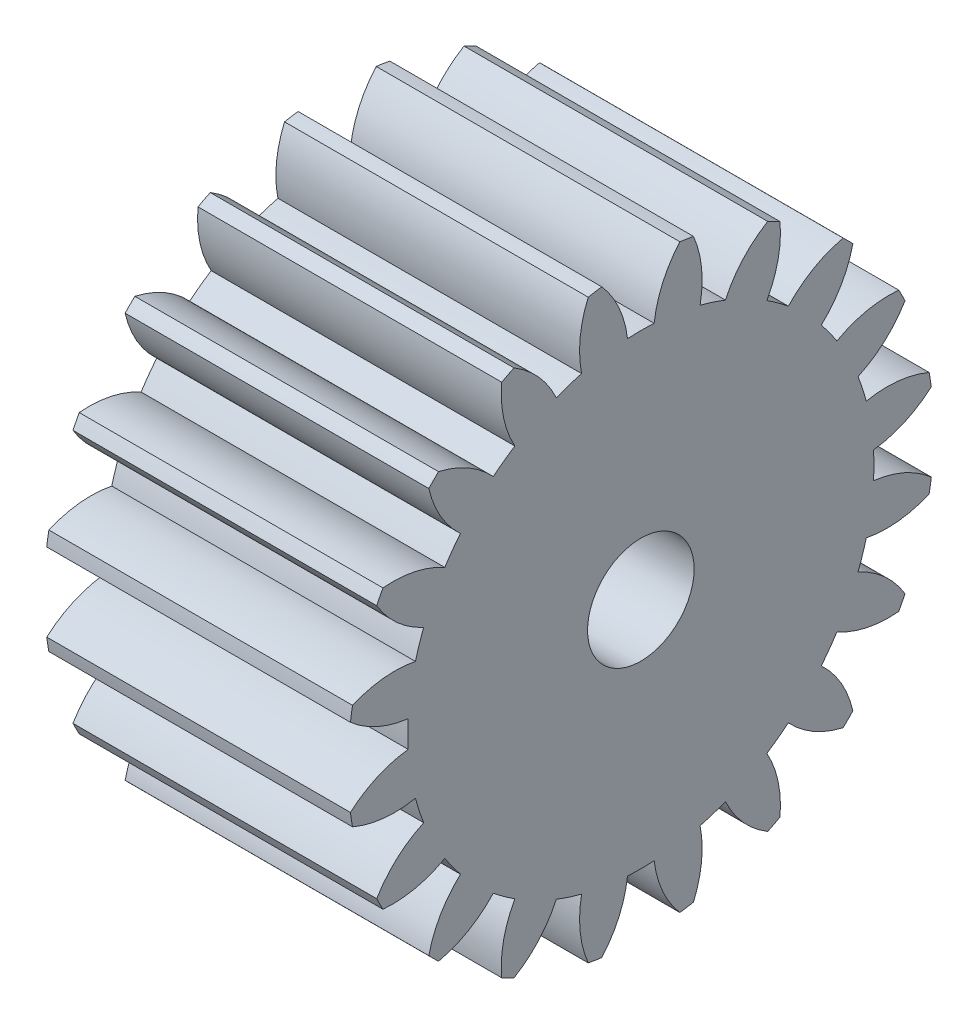
SolidWorks part; units mm, degrees
ref_plane "Plane1" through (0, 0, 0) normal (0, 0, 1) x (1, 0, 0)
ref_plane "Plane2" through (0, 0, 0) normal (0, 1, 0) x (1, 0, 0)
ref_plane "Plane3" through (0, 0, 0) normal (1, 0, 0) x (0, 0, -1)
other "Configuration Table"
sketch "HoldingSke" plane through (0, 0, 0) normal (0, 1, 0) x (1, 0, 0)
  line L0 (0, 0) -> (1.8794, -0.684)
  line L1 (-15, 0) -> (100, 0) construction
  line L2 (0, 0) -> (-2.1039, 2.3779)
  line L3 (0, 0) -> (-11.863, 4.5341)
  line L4 (0, 0) -> (8.1152, 2.9537)
  line L5 (0, 0) -> (-46.8476, -17.4728)
  line L6 (0, 0) -> (-4.7251, -3.188)
  line L7 (-2.1039, 2.3779) -> (8.6586, 51.2059)
  line L8 (-76.2, 54.61) -> (-76.1, 54.61)
  line L9 (-71.009, 38.7566) -> (-53.1078, 45.2721)
  line L10 (-76.2, 71.12) -> (104.1128, 71.12)
  line L11 (0, 0) -> (-5.7, 0)
  line L12 (-76.2, 101.6) -> (-76.181, 101.6)
  line L13 (24.9733, 27.94) -> (52.9518, 28.4284)
  line L14 (24.9733, 27.94) -> (24.9743, 27.94)
  line L15 (24.9733, 27.94) -> (100.4006, 29.5858)
  line L16 (-63.627, -0.5) -> (-12.827, -0.5)
  circle A0 centre (0, 0) radius 0.4
  circle A1 centre (0, 0) radius 4.374
  circle A2 centre (0, 0) radius 37.5
  circle A3 centre (0, 0) radius 0.4
  dimension "MHD" = 8.748
  dimension "Hub_dia" = 75
  dimension "Bore" = 0.8
  dimension "MBD" = 0.8
  dimension "Num_teeth" = 20
  dimension "Pitch" = 2
  dimension "Overall_len" = 50
  dimension "Show_teeth" = 20
  dimension "Thickness" = 5.7
  dimension "OAL" = 50.0001
  dimension "T_dim" = 0.1
  dimension "Ap" = 20
  dimension "H" = 19.05
  dimension "Pitch_radius" = 180.3128
  dimension "Width" = 5.7
  dimension "Backlash" = 0.019
  dimension "Addendum_fac" = 1
  dimension "Dedendum_fac" = 1.25
  dimension "Clearance_fac" = 0.25
  dimension "Dedendum_add" = 0.001
  dimension "Module" = 0.5
sketch "BasProSke" plane through (0, 0, 0) normal (0, 1, 0) x (1, 0, 0)
  line L0 (-10, 0) -> (60, 0) construction
  line L1 (0, 0) -> (0, 5.5)
  line L2 (0, 0) -> (5.7, 0)
  line L3 (5.7, 0) -> (5.7, 5.5)
  line L4 (5.7, 5.5) -> (0, 5.5)
  dimension "Thickness" = 5.7
  dimension "Diameter" = 11
revolve "Base-Revolve" add sketch "BasProSke" angle 360 about L0
sketch "TooCutSke" plane through (0, 0, 0) normal (1, 0, 0) x (0, 0, -1)
  line L1 (0, 0) -> (0, 107) construction
  line L2 (0, 0) -> (-0.4255, 4.9819) construction
  line L3 (0, 0) -> (-1.5603, 9.8514) construction
  line L4 (-0.4255, 4.9819) -> (-0.7802, 4.9257) construction
  arc A0 (0.2499, 4.3669) -> (-0.2499, 4.3669) centre (0, 0) ccw
  arc A1 (0.7528, 5.4739) -> (-0.7528, 5.4739) centre (0, 0) ccw
  circle A2 centre (0, 0) radius 5 construction
  circle A3 centre (0, 0) radius 4.6985 construction
  arc A4 (-0.2499, 4.3669) -> (-0.7528, 5.4739) centre (-2.2361, 4.1322) ccw
  arc A5 (0.7528, 5.4739) -> (0.2499, 4.3669) centre (2.2361, 4.1322) ccw
  dimension "Root_dia" = 8.748
  dimension "Overcut_dia" = 11.0508
  dimension "Pitch_dia" = 10
  dimension "Base_dia" = 9.3969
  dimension "Flank_rad" = 2
  dimension "Half_ang" = 9
  dimension "Half_CT" = 0.359
extrude "ToothCut" cut sketch "TooCutSke" along normal through all
fillet "Breaks" [suppressed] radius 0.01
fillet "RootFillets" [suppressed] radius 0.126
pattern_circular "TeethCuts" count 20 every 18 about axis through (-10, 0, 0) along (1, 0, 0) of "ToothCut", "RootFillets", "Breaks"
sketch "HubNeaOneSke" plane through (0, 0, 0) normal (-1, 0, 0) x (0, 0, 1)
  circle A0 centre (0, 0) radius 4.374
  dimension "Diameter" = 8.748
extrude "HubNearOne" [suppressed] add sketch "HubNeaOneSke" along normal blind 44.3001
sketch "HubNeaBotSke" plane through (0, 0, 0) normal (-1, 0, 0) x (0, 0, 1)
  circle A0 centre (0, 0) radius 4.374
  dimension "Diameter" = 8.748
extrude "HubNearBoth" [suppressed] add sketch "HubNeaBotSke" along normal blind 22.15
ref_plane "FarPln" through (5.7, 0, 0) normal (1, 0, 0) x (0, 0, -1)
sketch "HubFarSke" plane through (5.7, 0, 0) normal (1, 0, 0) x (0, 0, -1)
  circle A0 centre (0, 0) radius 4.374
  dimension "Diameter" = 8.748
extrude "HubFar" [suppressed] add sketch "HubFarSke" along normal blind 22.15
sketch "BorSke" plane through (0, 0, 0) normal (1, 0, 0) x (0, 0, -1)
  circle A0 centre (0, 0) radius 0.4
  dimension "Diameter" = 0.8
extrude "Bore" cut sketch "BorSke" along normal mid plane 100.0001
sketch "KeySke" plane through (0, 0, 0) normal (1, 0, 0) x (0, 0, -1)
  line L0 (-0.05, 0) -> (-0.05, 0.5)
  line L1 (-0.05, 0.5) -> (0.05, 0.5)
  line L2 (0.05, 0.5) -> (0.05, 0)
  line L3 (0, 0) -> (0, 34) construction
  line L4 (-0.05, 0) -> (0.05, 0)
  dimension "Offset" = 0.5
  dimension "Width" = 0.1
extrude "Keyway" [suppressed] cut sketch "KeySke" along normal mid plane 100.0001
pattern_circular "Keyway2" [suppressed] count 2 every 90 about axis through (-10, 0, 0) along (1, 0, 0)
sketch "草图1" plane through (5.7, 0, 0) normal (1, 0, 0) x (0, 0, -1)
  circle A0 centre (0, 0) radius 1
extrude "切除-拉伸1" cut sketch "草图1" against normal blind 10
equation "' \"Module@HoldingSke\" = 6.35"
equation "' \"Num_teeth@HoldingSke\" = 12"
equation "' \"Ap@HoldingSke\" =  20"
equation "' \"Ap@HoldingSke\" = 20"
equation "' \"Width@HoldingSke\" = 0.5 * 25.4"
equation "' \"Hub_dia@HoldingSke\"= 1 * 25.4"
equation "' \"Hub_dia@HoldingSke\" = 1 * 25.4"
equation "' \"Overall_len@HoldingSke\" = 1.0 * 25.4"
equation "' \"Bore@HoldingSke\" = 0.75 * 25.4"
equation "' \"T_dim@HoldingSke\" = 0.1 * 25.4"
equation "' \"Width@KeySke\" = 0.25 * 25.4"
equation "' \"Show_teeth@HoldingSke\" = 13"
equation "' \"Backlash@HoldingSke\" = 0.009 * 25.4"
equation "' \"Addendum_fac@HoldingSke\" = 1.0"
equation "' \"Dedendum_fac@HoldingSke\" = 1.25"
equation "' \"Dedendum_add@HoldingSke\" = 0.00005 * 25.4"
equation "' \"Clearance_fac@HoldingSke\" = 0.25"
equation "\"Pitch@HoldingSke\" = 1 / \"Module@HoldingSke\""
equation "\"Overcut_dia@TooCutSke\" = (\"Num_teeth@HoldingSke\" + 2 * \"Addendum_fac@HoldingSke\") / \"Pitch@HoldingSke\" + 0.002 * 25.4"
equation "\"Pitch_dia@TooCutSke\" = \"Num_teeth@HoldingSke\" / \"Pitch@HoldingSke\""
equation "\"Base_dia@TooCutSke\" = \"Num_teeth@HoldingSke\" / \"Pitch@HoldingSke\" * cos((\"Ap@HoldingSke\"  * 3.14159265 / 180))"
equation "\"Root_dia@TooCutSke\" = (\"Num_teeth@HoldingSke\" + 2) / \"Pitch@HoldingSke\" - 2 * (\"Addendum_fac@HoldingSke\" + \"Dedendum_fac@HoldingSke\") / \"Pitch@HoldingSke\" - \"Dedendum_add@HoldingSke\" * 2"
equation "\"Half_ang@TooCutSke\" = 180 / \"Num_teeth@HoldingSke\""
equation "\"Half_CT@TooCutSke\" = \"Num_teeth@HoldingSke\" / \"Pitch@HoldingSke\" * sin((3.14159265 / 2 / \"Num_teeth@HoldingSke\")) / 2 - 7 * \"Backlash@HoldingSke\" / 4"
equation "\"Flank_rad@TooCutSke\" = \"Num_teeth@HoldingSke\" / \"Pitch@HoldingSke\" / 5"
equation "\"Radius@RootFillets\" = \"Clearance_fac@HoldingSke\" / \"Pitch@HoldingSke\" + \"Dedendum_add@HoldingSke\""
equation "\"Break_rad@Breaks\" = 0.02 / \"Pitch@HoldingSke\""
equation "\"Thickness@HoldingSke\" = \"Width@HoldingSke\""
equation "\"OAL@HoldingSke\" = \"Thickness@HoldingSke\""
equation "\"MHD@HoldingSke\" = (\"Num_teeth@HoldingSke\" + 2) / \"Pitch@HoldingSke\" - 2 * (\"Addendum_fac@HoldingSke\" + \"Dedendum_fac@HoldingSke\")  / \"Pitch@HoldingSke\" - \"Dedendum_add@HoldingSke\" * 2"
equation "\"MBD@HoldingSke\" = (\"Num_teeth@HoldingSke\" + 2) / \"Pitch@HoldingSke\" - 2 * (\"Addendum_fac@HoldingSke\" + \"Dedendum_fac@HoldingSke\")  / \"Pitch@HoldingSke\" - \"Dedendum_add@HoldingSke\" * 2 - 0.002 * 25.4"
equation "\"MHD@HoldingSke\" = ((sgn( \"MHD@HoldingSke\" - \"Hub_dia@HoldingSke\" )-1)*( \"MHD@HoldingSke\" - \"Hub_dia@HoldingSke\" ))/-2+ \"Hub_dia@HoldingSke\""
equation "\"MBD@HoldingSke\" = ((sgn( \"MBD@HoldingSke\" - \"Bore@HoldingSke\" )-1)*( \"MBD@HoldingSke\" - \"Bore@HoldingSke\" ))/-2+ \"Bore@HoldingSke\""
equation "\"OAL@HoldingSke\" = ((sgn( \"OAL@HoldingSke\" - \"Overall_len@HoldingSke\" )+1)*( \"OAL@HoldingSke\" - \"Overall_len@HoldingSke\" ))/2 + \"Overall_len@HoldingSke\" + 0.000002 * 25.4"
equation "\"Num_teeth@TeethCuts\" = int( \"Show_teeth@HoldingSke\" ) + 1"
equation "\"Num_teeth@TeethCuts\" = ((sgn( \"Num_teeth@TeethCuts\" - \"Num_teeth@HoldingSke\" )-1)*( \"Num_teeth@TeethCuts\" - \"Num_teeth@HoldingSke\" ))/-2+ \"Num_teeth@HoldingSke\""
equation "\"Num_teeth@TeethCuts\" = ((sgn( \"Num_teeth@TeethCuts\" - 2.0)+1)*( \"Num_teeth@TeethCuts\" - 2.0))/2 +2.0"
equation "\"Angle@TeethCuts\" = 360.0 / \"Num_teeth@HoldingSke\""
equation "\"Diameter@BasProSke\" = (\"Num_teeth@HoldingSke\" + 2 * \"Addendum_fac@HoldingSke\") / \"Pitch@HoldingSke\""
equation "\"Thickness@BasProSke\"  = \"Thickness@HoldingSke\""
equation "' \"Fillet_rad@BasProSke\" =  \"Thickness@HoldingSke\" * 0.05"
equation "' \"Fillet_rad@BasProSke\" = \"Thickness@HoldingSke\" * 0.05"
equation "\"MHD@HoldingSke\" = ((sgn( \"MHD@HoldingSke\" - \"Root_dia@TooCutSke\" )-1)*( \"MHD@HoldingSke\" - \"Root_dia@TooCutSke\" ))/-2+ \"Root_dia@TooCutSke\""
equation "\"Diameter@HubNeaOneSke\" = \"MHD@HoldingSke\""
equation "\"Length@HubNearOne\" = \"OAL@HoldingSke\" - \"Thickness@BasProSke\""
equation "\"Diameter@HubNeaBotSke\" = \"MHD@HoldingSke\""
equation "\"Length@HubNearBoth\" = ( \"OAL@HoldingSke\" - \"Thickness@BasProSke\" ) / 2.0"
equation "\"Thickness@FarPln\" = \"Thickness@BasProSke\""
equation "\"Diameter@HubFarSke\" = \"MHD@HoldingSke\""
equation "\"Length@HubFar\" = ( \"OAL@HoldingSke\" - \"Thickness@BasProSke\" ) / 2.0"
equation "\"Diameter@BorSke\" = \"MBD@HoldingSke\""
equation "\"D1@Bore\" = \"OAL@HoldingSke\" * 2.0"
equation "\"D1@Keyway\" = \"OAL@HoldingSke\" * 2.0"
equation "\"Offset@KeySke\" = \"T_dim@HoldingSke\" + \"MBD@HoldingSke\" / 2.0"
